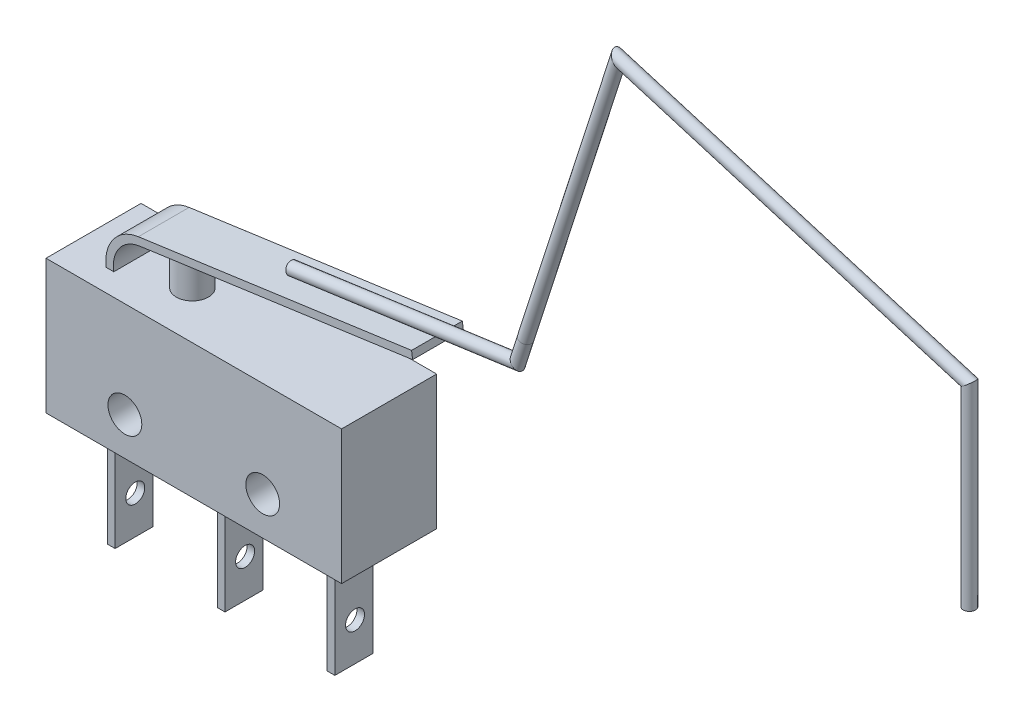
SolidWorks part; units mm, degrees
ref_plane "Front Plane" through (0, 0, 0) normal (0, 0, 1) x (1, 0, 0)
ref_plane "Top Plane" through (0, 0, 0) normal (0, 1, 0) x (1, 0, 0)
ref_plane "Right Plane" through (0, 0, 0) normal (1, 0, 0) x (0, 0, -1)
sketch "Sketch1" plane through (0, 0, 0) normal (0, 0, 1) x (1, 0, 0)
  line L0 (-4.6037, -1.9367) -> (4.6037, -1.9367) construction
  line L1 (-9.8742, -4.4768) -> (9.8743, -4.4768)
  line L2 (-9.8742, -4.4768) -> (-9.8742, 4.4768)
  line L3 (-9.8742, 4.4768) -> (9.8743, 4.4768)
  line L4 (9.8743, -4.4768) -> (9.8743, 4.4768)
  line L5 (-9.8742, -4.4768) -> (9.8743, 4.4768) construction
  line L6 (-9.8742, 4.4768) -> (9.8743, -4.4768) construction
  circle A0 centre (-4.6037, -1.9367) radius 1.1303
  circle A1 centre (4.6037, -1.9367) radius 1.1303
  point P0 (0, 0)
  point P10 (0, -1.9367)
  dimension "D5" = 2.2606
  dimension "D1" = 8.9535
  dimension "D2" = 19.7485
  dimension "D3" = 9.2075
  dimension "D4" = 2.54
extrude "Boss-Extrude1" add sketch "Sketch1" along normal mid plane 6.35
sketch "Sketch8" plane through (0, 0, 3.175) normal (0, 0, 1) x (1, 0, 0)
  line L0 (0, 10.6108) -> (0, 0) construction
  line L1 (-9.8742, 4.4768) -> (-9.8742, -4.4768) construction
  line L2 (9.8743, 4.4768) -> (-9.8742, 4.4768) construction
  line L8 (15.875, 10.6108) -> (15.875, 12.7063) construction
  line L9 (15.875, 12.7063) -> (13.7033, 12.7063) construction
  line L11 (13.7033, 10.6108) -> (15.875, 10.6108) construction
  line L13 (-9.8742, -4.4768) -> (9.8743, -4.4768) construction
  line L14 (9.8743, -4.4768) -> (9.8743, 4.4768) construction
  line L24 (2.1145, 10.6108) -> (-2.1146, 10.6108) construction
  line L25 (-2.1146, 10.6108) -> (-2.1146, 12.7063) construction
  line L26 (-2.1146, 12.7063) -> (-13.7033, 12.7063) construction
  line L28 (-13.7033, 10.6108) -> (-10.4966, 10.6108) construction
  line L29 (-10.4966, 10.6108) -> (-10.4966, -5.2642) construction
  line L30 (-10.4966, -5.2642) -> (10.4966, -5.2642) construction
  line L31 (10.4966, -5.2642) -> (10.4966, 10.6108) construction
  line L32 (10.4966, 10.6108) -> (13.7033, 10.6108) construction
  line L33 (13.7033, 10.6108) -> (13.7033, 12.7063) construction
  line L34 (13.7033, 12.7063) -> (2.1146, 12.7063) construction
  line L35 (2.1146, 12.7063) -> (2.1145, 10.6108) construction
  line L36 (-15.875, 12.7063) -> (-15.875, 10.6108) construction
  line L37 (-15.875, 10.6108) -> (-13.7033, 10.6108) construction
  line L38 (-13.7033, 10.6108) -> (-13.7033, 12.7063) construction
  line L39 (-13.7033, 12.7063) -> (-15.875, 12.7063) construction
  point P22 (0, -5.2642)
  point P24 (0, 10.6108)
  dimension "D1" = 15.875
  dimension "D2" = 31.75
  dimension "D3" = 4.2291
  dimension "D4" = 11.5888
  dimension "D5" = 2.1717
  dimension "D6" = 2.0955
  dimension "D8" = 0.7874
  dimension "D9" = 0.6223
sketch "Sketch6" plane through (0, 0, 0) normal (0, 0, 1) x (1, 0, 0)
  line L0 (0, 12.7063) -> (0, 0) construction
  line L1 (0, 12.7063) -> (18.9992, 12.7063) construction
  line L2 (13.7033, 12.7063) -> (2.1146, 12.7063) construction
  line L3 (18.9992, 12.7063) -> (25.2095, 32.0103)
  line L8 (25.2095, 32.0103) -> (48.641, 24.9618)
  line L10 (48.641, 24.9618) -> (48.641, 11.9951)
  line L11 (18.9992, 12.7063) -> (18.4721, 11.068)
  line L12 (18.4721, 11.068) -> (3.3787, 8.9598)
  dimension "D1" = 18.9992
  dimension "D2" = 19.304
  dimension "D3" = 6.2103
  dimension "D4" = 29.6418
  dimension "D5" = 12.2555
  dimension "D6" = 0.7112
  dimension "D7" = 29.6418
  dimension "D8" = 1.6383
  dimension "D9" = 15.24
  dimension "D10" = 3.7465
ref_plane "Plane1" through (0, 0, 1.3462) normal (0, 0, 1) x (1, 0, 0)
sketch "Sketch2" plane through (0, 0, 1.3462) normal (0, 0, 1) x (1, 0, 0)
  line L0 (-9.8742, -4.4768) -> (9.8743, -4.4768) construction
  line L1 (-7.5946, -4.4768) -> (-7.0866, -4.4768)
  line L2 (-7.5946, -4.4768) -> (-7.5946, -11.8427)
  line L3 (-7.5946, -11.8427) -> (-7.0866, -11.8427)
  line L4 (-7.0866, -4.4768) -> (-7.0866, -11.8427)
  line L5 (0, 0) -> (0, -4.4768) construction
  line L6 (-0.254, -4.4767) -> (0.254, -4.4767)
  line L7 (-0.254, -4.4767) -> (-0.254, -11.8427)
  line L8 (-0.254, -11.8427) -> (0.254, -11.8427)
  line L9 (0.254, -4.4767) -> (0.254, -11.8427)
  line L10 (7.0866, -4.4767) -> (7.5946, -4.4767)
  line L11 (7.0866, -4.4767) -> (7.0866, -11.8427)
  line L12 (7.0866, -11.8427) -> (7.5946, -11.8427)
  line L13 (7.5946, -4.4767) -> (7.5946, -11.8427)
  point P17 (0, -4.4767)
  dimension "D1" = 7.366
  dimension "D2" = 0.508
  dimension "D3" = 6.8326
extrude "Boss-Extrude2" add sketch "Sketch2" against normal blind 2.54
sketch "Sketch3" plane through (-7.5946, 0, 0) normal (-1, 0, 0) x (0, 0, 1)
  line L0 (-1.1938, -11.8427) -> (1.3462, -11.8427) construction
  circle A0 centre (0, -9.3027) radius 0.635
  dimension "D1" = 1.27
  dimension "D2" = 2.54
extrude "Cut-Extrude1" cut sketch "Sketch3" against normal through all
sketch "Sketch4" plane through (0, 0, 0) normal (0, 0, 1) x (1, 0, 0)
  line L0 (-5.1818, 7.3282) -> (13.0698, 9.8775)
  line L1 (13.0698, 9.8775) -> (13.1401, 9.3744)
  line L2 (13.1401, 9.3744) -> (-5.1074, 6.8256)
  line L3 (9.8743, 4.4768) -> (-9.8742, 4.4768) construction
  line L4 (-9.8742, 4.4768) -> (-9.8742, -4.4768) construction
  line L5 (-7.3342, 4.4768) -> (-7.6837, 6.9787) construction
  line L6 (-7.6837, 6.9787) -> (-5.1818, 7.3282) construction
  line L7 (-7.3342, 4.4768) -> (-6.8262, 4.4768)
  line L8 (-6.8486, 6.3483) -> (-6.4436, 6.0415) construction
  line L9 (-6.2181, 7.1834) -> (-7.479, 5.5131) construction
  line L10 (18.4721, 11.068) -> (3.3787, 8.9598) construction
  arc A0 (-5.1818, 7.3282) -> (-7.3342, 4.4768) centre (-4.8323, 4.8262) ccw
  arc A1 (-5.1074, 6.8256) -> (-6.8262, 4.4768) centre (-4.8269, 4.817) ccw
  point P18 (-6.8486, 6.3483)
  dimension "D1" = 2.54
  dimension "D2" = 20.955
  dimension "D3" = 0.508
  dimension "D4" = 0.4318
extrude "Boss-Extrude3" add sketch "Sketch4" along normal mid plane 3.3909
sketch "Sketch5" plane through (0, 4.4768, 0) normal (0, 1, 0) x (1, 0, 0)
  line L0 (-9.8742, -3.175) -> (-9.8742, 3.175) construction
  circle A0 centre (-3.2702, 0) radius 1.0732
  dimension "D1" = 2.1463
  dimension "D2" = 6.604
extrude "Boss-Extrude4" add sketch "Sketch5" along normal up to surface (2.6055 mm away)
ref_plane "Plane2" through (4.5415, 0.6343, 0) normal (0.9904, 0.1383, 0) x (0, 0, -1)
sketch "Sketch7" plane through (4.5415, 0.6343, 0) normal (0.9904, 0.1383, 0) x (0, 0, -1)
  circle A0 centre (0, 8.4063) radius 0.4064
  dimension "D1" = 0.8128
sweep "Sweep1" add profiles "Sketch7" path "Sketch6"
ref_plane "Plane3" through (25.2095, 0, 0) normal (1, 0, 0) x (0, 0, -1)
